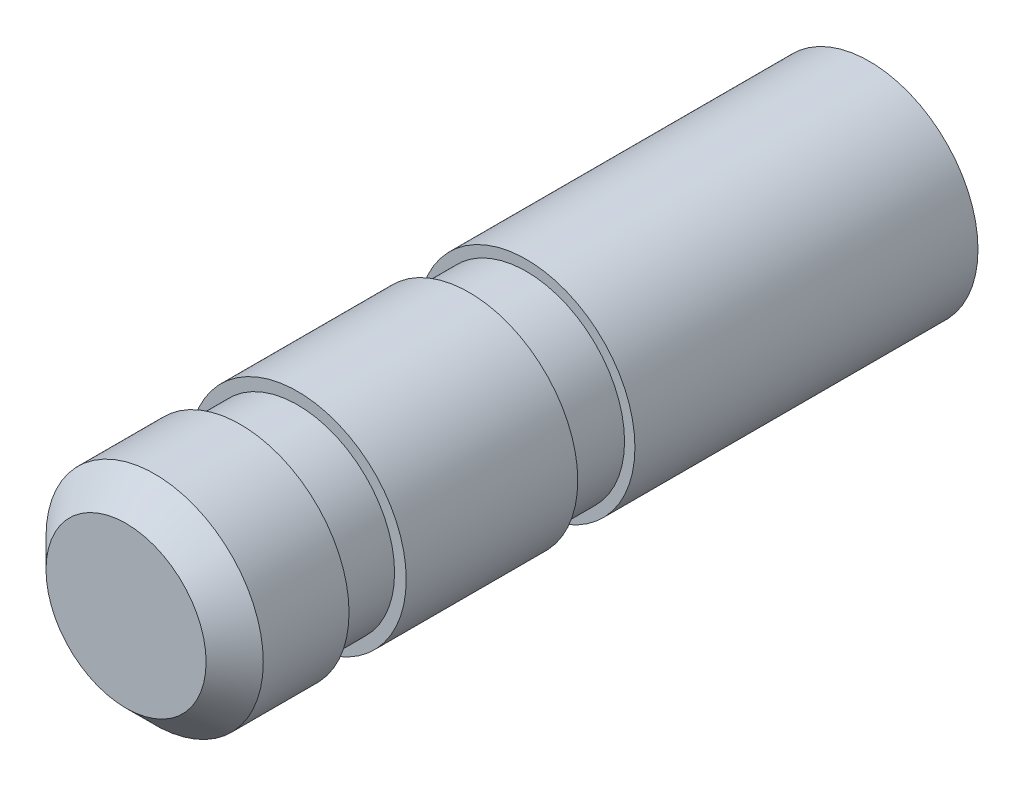
SolidWorks part; units mm, degrees
ref_plane "Front Plane" through (0, 0, 0) normal (0, 0, 1) x (1, 0, 0)
ref_plane "Top Plane" through (0, 0, 0) normal (0, 1, 0) x (1, 0, 0)
ref_plane "Right Plane" through (0, 0, 0) normal (1, 0, 0) x (0, 0, -1)
sketch "Sketch1" plane through (0, 0, 0) normal (0, 0, 1) x (1, 0, 0)
  circle A0 centre (0, 0) radius 1.9
  dimension "D1" = 3.8
extrude "Boss-Extrude1" add sketch "Sketch1" along normal blind 13 contours A0
chamfer "Chamfer1" distance 0.5 angle 45 1 edges at (1.9, 0, 13)
sketch "Sketch4" plane through (0, 0, 0) normal (1, 0, 0) x (0, 0, -1)
  line L0 (-14.9535, 0) -> (2.3388, 0) construction
  line L1 (0, 1.9) -> (-12.5, 1.9) construction
  line L2 (-11, 1.6963) -> (-10, 1.6963)
  line L3 (-11, 1.6963) -> (-11, 2.1037)
  line L4 (-11, 2.1037) -> (-10, 2.1037)
  line L5 (-10, 1.6963) -> (-10, 2.1037)
  line L6 (-11, 1.6963) -> (-10, 2.1037) construction
  line L7 (-11, 2.1037) -> (-10, 1.6963) construction
  line L8 (-13, 1.4) -> (-13, -1.4) construction
  point P3 (-10.5, 1.9)
  dimension "D1" = 1
  dimension "D2" = 2
revolve "Cut-Revolve4" cut sketch "Sketch4" angle 360 about L0
sketch "Sketch7" plane through (0, 0, 0) normal (1, 0, 0) x (0, 0, -1)
  line L0 (-14.337, 0) -> (2.3696, 0) construction
  line L1 (0, 1.9) -> (-10, 1.9) construction
  line L2 (-7, 2.0816) -> (-6, 2.0816)
  line L3 (-7, 2.0816) -> (-7, 1.7184)
  line L4 (-7, 1.7184) -> (-6, 1.7184)
  line L5 (-6, 2.0816) -> (-6, 1.7184)
  line L6 (-7, 2.0816) -> (-6, 1.7184) construction
  line L7 (-7, 1.7184) -> (-6, 2.0816) construction
  line L8 (-10, 1.6963) -> (-10, -1.6963) construction
  point P3 (-6.5, 1.9)
  dimension "D1" = 1
  dimension "D2" = 3
revolve "Cut-Revolve7" cut sketch "Sketch7" angle 360 about L0
